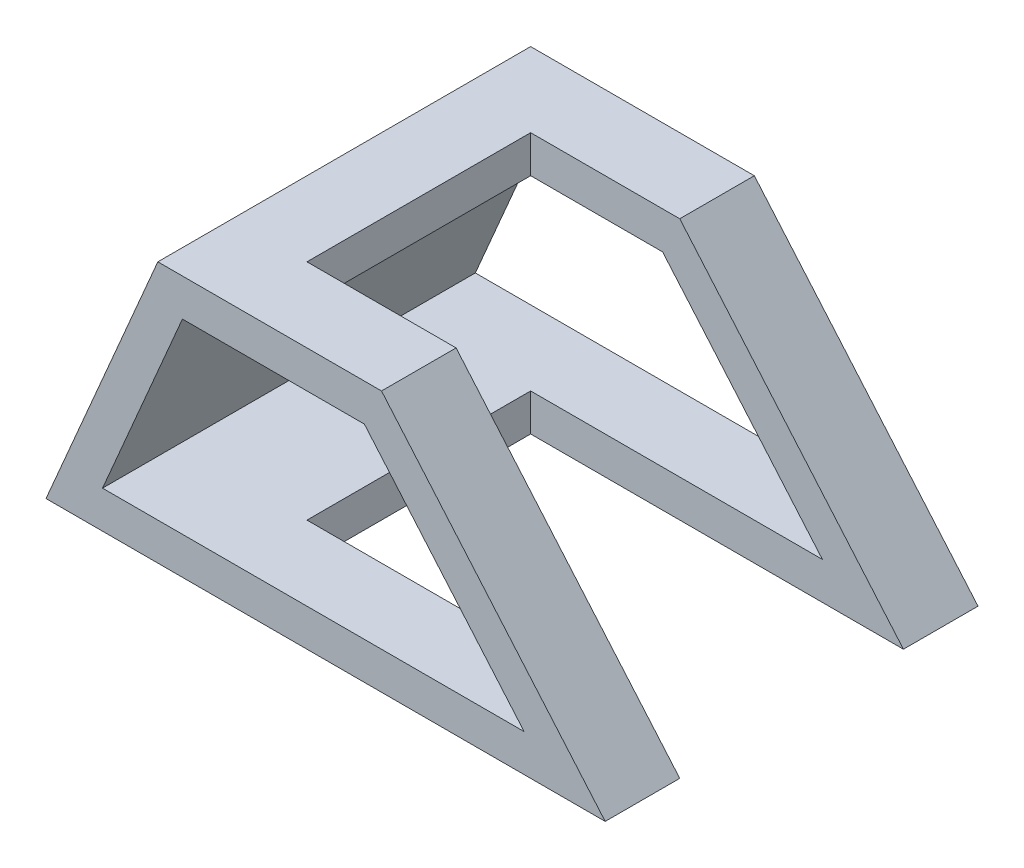
SolidWorks part; units mm, degrees
ref_plane "Front Plane" through (0, 0, 0) normal (0, 0, 1) x (1, 0, 0)
ref_plane "Top Plane" through (0, 0, 0) normal (0, 1, 0) x (1, 0, 0)
ref_plane "Right Plane" through (0, 0, 0) normal (1, 0, 0) x (0, 0, -1)
sketch "Sketch1" plane through (0, 0, 0) normal (0, 0, 1) x (1, 0, 0)
  line L0 (-75.4188, 0) -> (74.5812, 0)
  line L1 (74.5812, 0) -> (14.5812, 70)
  line L2 (14.5812, 70) -> (-45.4188, 70)
  line L3 (-45.4188, 70) -> (-75.4188, 0)
  line L4 (9.9819, 60) -> (-38.8248, 60)
  line L5 (-38.8248, 60) -> (-60.2534, 10)
  line L6 (-60.2534, 10) -> (52.839, 10)
  line L7 (52.839, 10) -> (9.9819, 60)
  dimension "D1" = 70
  dimension "D2" = 60
  dimension "D3" = 150
  dimension "D4" = 30
  dimension "D5" = 60
  dimension "D6" = 10
extrude "Boss-Extrude1" add sketch "Sketch1" along normal blind 100
sketch "Sketch2" plane through (0, 70, 0) normal (0, 1, 0) x (1, 0, 0)
  line L0 (74.5812, -100) -> (74.5812, 0) construction
  line L1 (-25.4188, -20) -> (74.5812, -20)
  line L2 (-25.4188, -20) -> (-25.4188, -80)
  line L3 (-25.4188, -80) -> (74.5812, -80)
  line L4 (74.5812, -20) -> (74.5812, -80)
  line L5 (-25.4188, -20) -> (74.5812, -80) construction
  line L6 (-25.4188, -80) -> (74.5812, -20) construction
  line L7 (74.5812, 0) -> (14.5812, 0) construction
  line L9 (74.5812, -100) -> (14.5812, -100) construction
  point P0 (24.5812, -50)
  dimension "D1" = 100
  dimension "D2" = 60
  dimension "D3" = 20
  dimension "D4" = 20
extrude "Cut-Extrude1" cut sketch "Sketch2" against normal up to surface (70 mm away) up to face at (-0.4188, 0, 50)
